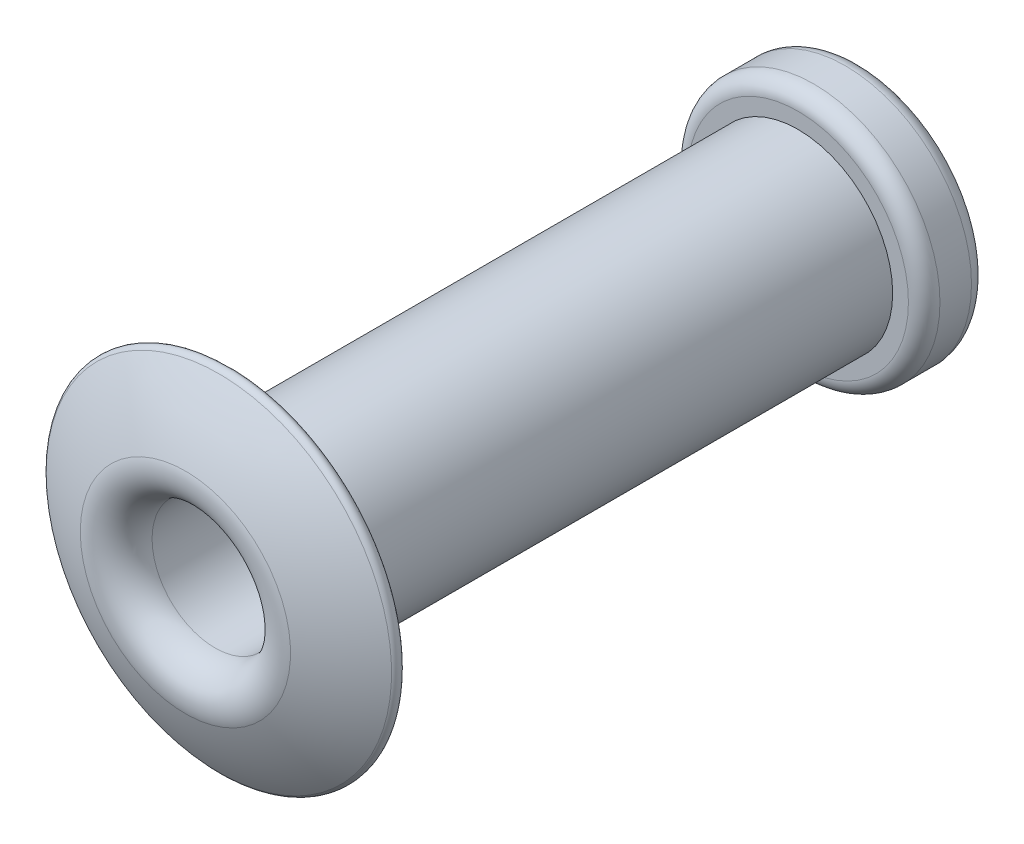
SolidWorks part; units mm, degrees
ref_plane "正面" through (0, 0, 0) normal (0, 0, 1) x (1, 0, 0)
ref_plane "平面" through (0, 0, 0) normal (0, 1, 0) x (1, 0, 0)
ref_plane "右側面" through (0, 0, 0) normal (1, 0, 0) x (0, 0, -1)
sketch "ｽｹｯﾁ1" plane through (0, 0, 0) normal (0, 1, 0) x (1, 0, 0)
  line L0 (0, -5.5) -> (0, 5.5)
  line L1 (0, 5.5) -> (2, 5.5)
  line L2 (2, 5.5) -> (2, 4.5)
  line L3 (2, 4.5) -> (1.5, 4.5)
  line L4 (1.5, 4.5) -> (1.5, -4.5)
  line L5 (1.5, -4.5) -> (3, -4.5)
  arc A0 (0, -5.5) -> (3, -4.5) centre (0, -0.5) ccw
  point P4 (0, 0)
  dimension "D1" = 11
  dimension "D2" = 1.5
  dimension "D3" = 2
  dimension "D4" = 1
  dimension "D5" = 3
  dimension "D6" = 1
revolve "回転1" add sketch "ｽｹｯﾁ1" angle 360 about L0
sketch "ｽｹｯﾁ2" plane through (0, 0, -5.5) normal (0, 0, -1) x (-1, 0, 0)
  circle A0 centre (0, 0) radius 1
  dimension "D1" = 2
extrude "ｶｯﾄ - 押し出し1" cut sketch "ｽｹｯﾁ2" against normal through all
fillet "ﾌｨﾚｯﾄ1" radius 0.25 2 edges at (2, 0, -4.5) (2, 0, -5.5)
fillet "ﾌｨﾚｯﾄ2" radius 0.1 1 edges at (3, 0, 4.5)
fillet "ﾌｨﾚｯﾄ3" radius 0.5 2 edges at (-1, 0, -5.5) (-1, 0, 5.399)
